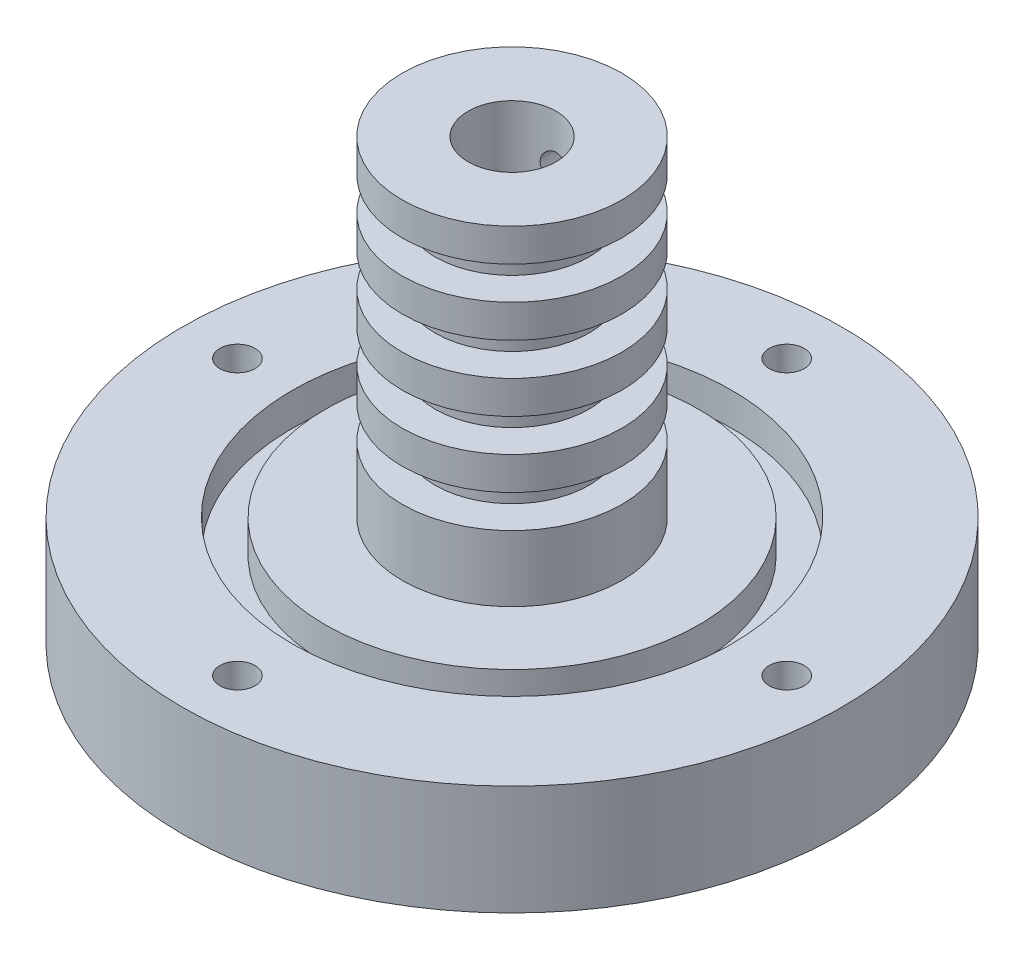
SolidWorks part; units mm, degrees
ref_plane "Front Plane" through (0, 0, 0) normal (0, 0, 1) x (1, 0, 0)
ref_plane "Top Plane" through (0, 0, 0) normal (0, 1, 0) x (1, 0, 0)
ref_plane "Right Plane" through (0, 0, 0) normal (1, 0, 0) x (0, 0, -1)
sketch "Sketch2" plane through (0, 0, 0) normal (0, 0, 1) x (1, 0, 0)
  line L0 (0, 37.556) -> (0, -45.6193) construction
  line L1 (4, 35.9683) -> (4, -4.0317)
  line L3 (4, 35.9683) -> (10, 35.9683)
  line L4 (10, 35.9683) -> (10, 32.9683)
  line L5 (10, 32.9683) -> (7, 32.9683)
  line L6 (7, 32.9683) -> (7, 29.9683)
  line L7 (7, 29.9683) -> (10, 29.9683)
  line L8 (10, 29.9683) -> (10, 26.9683)
  line L9 (10, 26.9683) -> (7, 26.9683)
  line L10 (7, 26.9683) -> (7, 23.9683)
  line L11 (7, 23.9683) -> (10, 23.9683)
  line L12 (10, 23.9683) -> (10, 20.9683)
  line L13 (10, 20.9683) -> (7, 20.9683)
  line L14 (7, 20.9683) -> (7, 17.9683)
  line L15 (7, 17.9683) -> (10, 17.9683)
  line L16 (10, 17.9683) -> (10, 14.9683)
  line L17 (10, 14.9683) -> (7, 14.9683)
  line L18 (7, 14.9683) -> (7, 11.9683)
  line L19 (7, 11.9683) -> (10, 11.9683)
  line L20 (10, 11.9683) -> (10, 5.9683)
  line L21 (10, 5.9683) -> (17, 5.9683)
  line L22 (17, 5.9683) -> (17, 2.9683)
  line L23 (17, 2.9683) -> (20, 2.9683)
  line L24 (20, 2.9683) -> (20, 5.9683)
  line L25 (20, 5.9683) -> (30, 5.9683)
  line L26 (30, 5.9683) -> (30, -4.0317)
  line L27 (30, -4.0317) -> (4, -4.0317)
revolve "Revolve1" add sketch "Sketch2" angle 360 about L0
sketch "Sketch5" plane through (0, 5.9683, 0) normal (0, 1, 0) x (1, 0, 0)
  line L0 (-30, 0) -> (30, 0) construction
  circle A0 centre (0, 0) radius 30 construction
  circle A1 centre (-25, 0) radius 1.6
  circle A2 centre (0, 25) radius 1.6
  circle A3 centre (25, 0) radius 1.6
  circle A4 centre (0, -25) radius 1.6
  point P16 (0, 0)
  dimension "D1" = 4
extrude "Cut-Extrude2" cut sketch "Sketch5" against normal blind 10 contours A4 | A1 | A2 | A3
sketch "Sketch8" plane through (0, 0, 0) normal (0, 0, 1) x (1, 0, 0)
  circle A0 centre (0, 31.4683) radius 1.25
  circle A1 centre (0, 25.4683) radius 1.25
  circle A2 centre (0, 19.4683) radius 1.25
  circle A3 centre (0, 13.4683) radius 1.25
  dimension "D1" = 4
extrude "Cut-Extrude3" cut sketch "Sketch8" against normal blind 10
